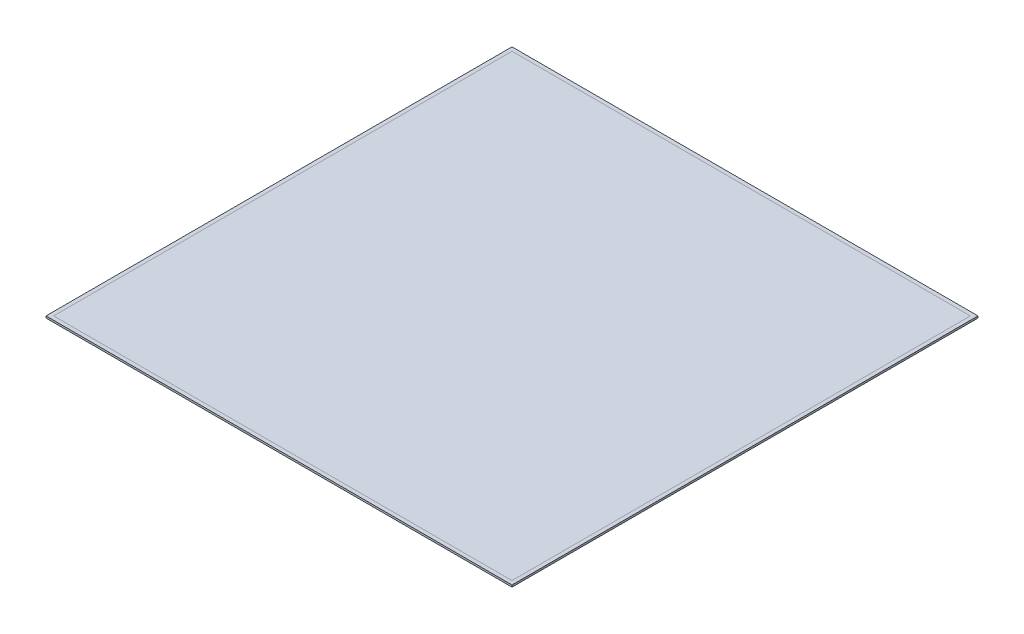
SolidWorks part; units mm, degrees
ref_plane "前视基准面" through (0, 0, 0) normal (0, 0, 1) x (1, 0, 0)
ref_plane "上视基准面" through (0, 0, 0) normal (0, 1, 0) x (1, 0, 0)
ref_plane "右视基准面" through (0, 0, 0) normal (1, 0, 0) x (0, 0, -1)
sketch "草图4" plane through (0, 0, 0) normal (0, 1, 0) x (1, 0, 0)
  line L1 (-1200, 1200) -> (1200, 1200)
  line L2 (-1200, 1200) -> (-1200, -1200)
  line L3 (-1200, -1200) -> (1200, -1200)
  line L4 (1200, 1200) -> (1200, -1200)
  line L5 (-1200, 1200) -> (1200, -1200) construction
  line L6 (-1200, -1200) -> (1200, 1200) construction
  line L7 (-1220, 1220) -> (1220, 1220)
  line L8 (-1220, 1220) -> (-1220, -1220)
  line L9 (-1220, -1220) -> (1220, -1220)
  line L10 (1220, 1220) -> (1220, -1220)
  line L11 (-1220, 1220) -> (1220, -1220) construction
  line L12 (-1220, -1220) -> (1220, 1220) construction
  point P0 (0, 0)
  point P6 (0, 0)
  dimension "D1" = 2400
  dimension "D2" = 2400
  dimension "D3" = 20
  dimension "D4" = 20
extrude "凸台-拉伸4" add sketch "草图4" along normal blind 10
sketch "草图5" plane through (0, 10, 0) normal (0, 1, 0) x (1, 0, 0)
  line L1 (1200, 1200) -> (-1200, 1200)
  line L2 (1200, 1200) -> (1200, -1200)
  line L3 (1200, -1200) -> (-1200, -1200)
  line L4 (-1200, 1200) -> (-1200, -1200)
  line L5 (1200, 1200) -> (-1200, -1200) construction
  line L6 (1200, -1200) -> (-1200, 1200) construction
  point P0 (0, 0)
extrude "凸台-拉伸6" add sketch "草图5" against normal blind 10 separate body
sketch "草图6" plane through (0, 0, 0) normal (0, -1, 0) x (1, 0, 0)
  line L1 (1200, 1200) -> (900, 1200)
  line L2 (1200, 1200) -> (1200, 900)
  line L3 (1200, 900) -> (900, 900)
  line L4 (900, 1200) -> (900, 900)
  dimension "D1" = 300
  dimension "D2" = 300
extrude "凸台-拉伸9" add sketch "草图6" along normal blind 0.1 separate body
sketch "草图7" plane through (0, 0, 0) normal (0, -1, 0) x (1, 0, 0)
  line L1 (1200, -1200) -> (900, -1200)
  line L2 (1200, -1200) -> (1200, -900)
  line L3 (1200, -900) -> (900, -900)
  line L4 (900, -1200) -> (900, -900)
  dimension "D1" = 300
  dimension "D2" = 300
extrude "凸台-拉伸10" add sketch "草图7" along normal blind 0.1 separate body
sketch "草图8" plane through (0, 0, 0) normal (0, -1, 0) x (1, 0, 0)
  line L1 (-400, 400) -> (400, 400)
  line L2 (-400, 400) -> (-400, -400)
  line L3 (-400, -400) -> (400, -400)
  line L4 (400, 400) -> (400, -400)
  line L5 (-400, 400) -> (400, -400) construction
  line L6 (-400, -400) -> (400, 400) construction
  point P0 (0, 0)
  dimension "D1" = 800
  dimension "D2" = 800
extrude "凸台-拉伸11" add sketch "草图8" along normal blind 0.1 separate body
sketch "草图9" plane through (0, 0, 0) normal (0, -1, 0) x (1, 0, 0)
  line L0 (400, -400) -> (400, 400) construction
  line L1 (-400, 400) -> (400, 400)
  line L2 (-400, 400) -> (-400, -400)
  line L3 (-400, -400) -> (400, -400)
  line L4 (400, 400) -> (400, -400)
  line L5 (-400, 400) -> (400, -400) construction
  line L6 (-400, -400) -> (400, 400) construction
  line L7 (-400, -400) -> (400, -400) construction
  line L8 (-420, 420) -> (420, 420)
  line L9 (-420, 420) -> (-420, -420)
  line L10 (-420, -420) -> (420, -420)
  line L11 (420, 420) -> (420, -420)
  line L12 (-420, 420) -> (420, -420) construction
  line L13 (-420, -420) -> (420, 420) construction
  point P0 (0, 0)
  point P8 (0, 0)
  dimension "D1" = 20
  dimension "D2" = 20
extrude "凸台-拉伸13" add sketch "草图9" along normal blind 0.1 separate body
